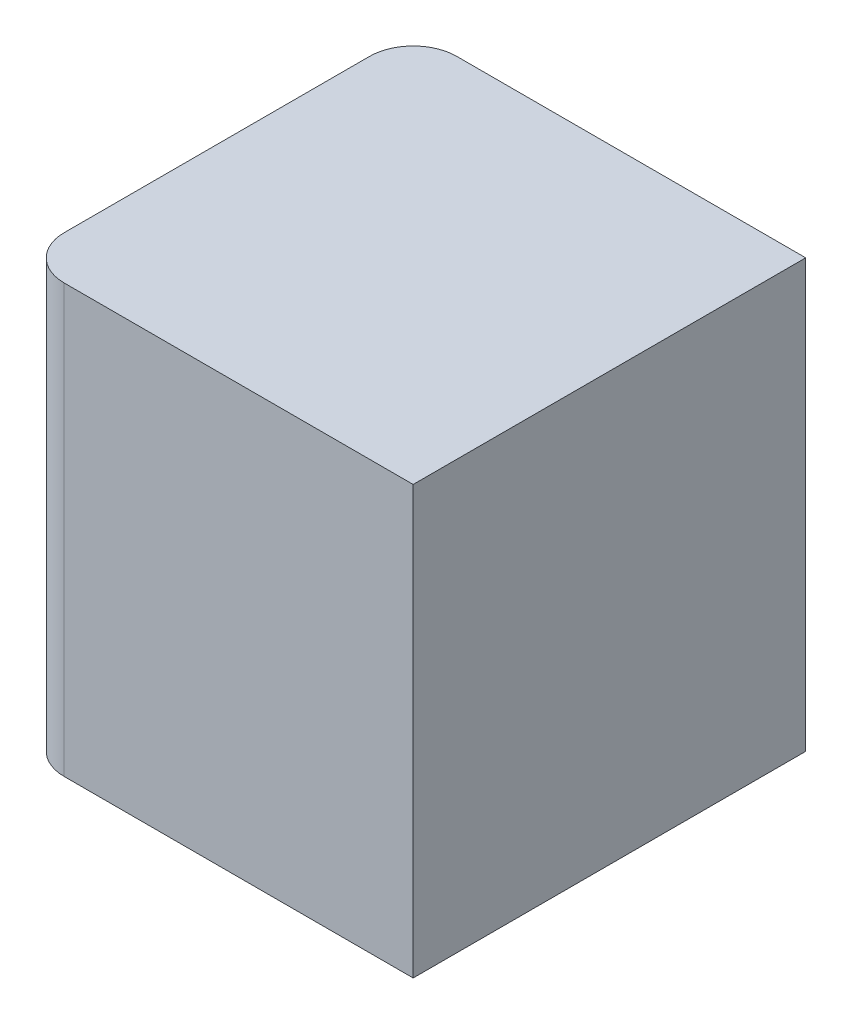
SolidWorks part; units mm, degrees
ref_plane "Front Plane" through (0, 0, 0) normal (0, 0, 1) x (1, 0, 0)
ref_plane "Top Plane" through (0, 0, 0) normal (0, 1, 0) x (1, 0, 0)
ref_plane "Right Plane" through (0, 0, 0) normal (1, 0, 0) x (0, 0, -1)
sketch "Sketch1" plane through (0, 0, 0) normal (0, 1, 0) x (1, 0, 0)
  line L1 (0, 0) -> (22.86, 0)
  line L2 (0, 0) -> (0, -22.86)
  line L3 (0, -22.86) -> (22.86, -22.86)
  line L4 (22.86, 0) -> (22.86, -22.86)
  dimension "D1" = 22.86
  dimension "D2" = 22.86
extrude "Boss-Extrude1" add sketch "Sketch1" along normal blind 24.892
fillet "Fillet1" radius 2.54 2 edges at (0, 12.446, 22.86) (0, 12.446, 0)
